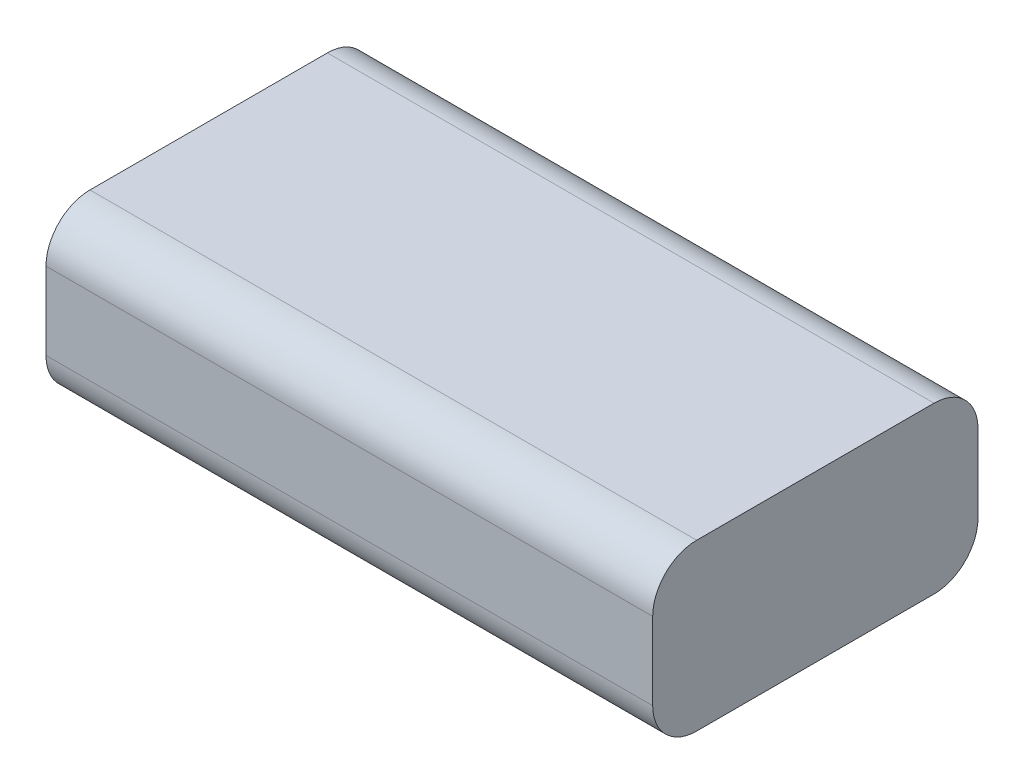
SolidWorks part; units mm, degrees
ref_plane "前视基准面" through (0, 0, 0) normal (0, 0, 1) x (1, 0, 0)
ref_plane "上视基准面" through (0, 0, 0) normal (0, 1, 0) x (1, 0, 0)
ref_plane "右视基准面" through (0, 0, 0) normal (1, 0, 0) x (0, 0, -1)
sketch "草图1" plane through (0, 0, 0) normal (0, 1, 0) x (1, 0, 0)
  line L1 (-34.5, -18.5) -> (34.5, -18.5)
  line L2 (-34.5, -18.5) -> (-34.5, 18.5)
  line L3 (-34.5, 18.5) -> (34.5, 18.5)
  line L4 (34.5, -18.5) -> (34.5, 18.5)
  line L5 (-34.5, -18.5) -> (34.5, 18.5) construction
  line L6 (-34.5, 18.5) -> (34.5, -18.5) construction
  point P0 (0, 0)
  dimension "D1" = 69
  dimension "D2" = 37
extrude "凸台-拉伸1" add sketch "草图1" along normal blind 18.8
fillet "圆角1" radius 5 4 edges at (0, 0, -18.5) (0, 0, 18.5) (0, 18.8, 18.5) (0, 18.8, -18.5)
